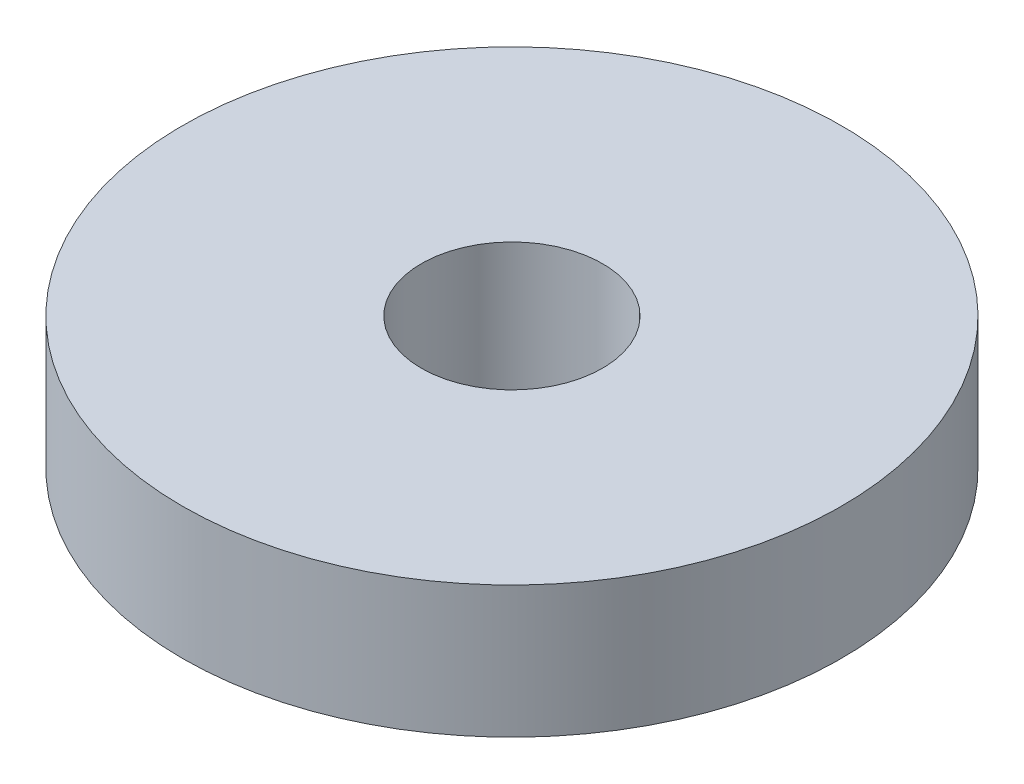
SolidWorks part; units mm, degrees
ref_plane "Front Plane" through (0, 0, 0) normal (0, 0, 1) x (1, 0, 0)
ref_plane "Top Plane" through (0, 0, 0) normal (0, 1, 0) x (1, 0, 0)
ref_plane "Right Plane" through (0, 0, 0) normal (1, 0, 0) x (0, 0, -1)
sketch "Sketch1" plane through (0, 0, 0) normal (0, 1, 0) x (1, 0, 0)
  circle A2 centre (0, 0) radius 100
  dimension "D2" = 200
extrude "Boss-Extrude1" add sketch "Sketch1" along normal blind 40 contours A2
sketch "Sketch2" plane through (0, 40, 0) normal (0, 1, 0) x (1, 0, 0)
  circle A0 centre (0, 0) radius 27.5
  dimension "D1" = 55
extrude "Cut-Extrude1" cut sketch "Sketch2" against normal through all
